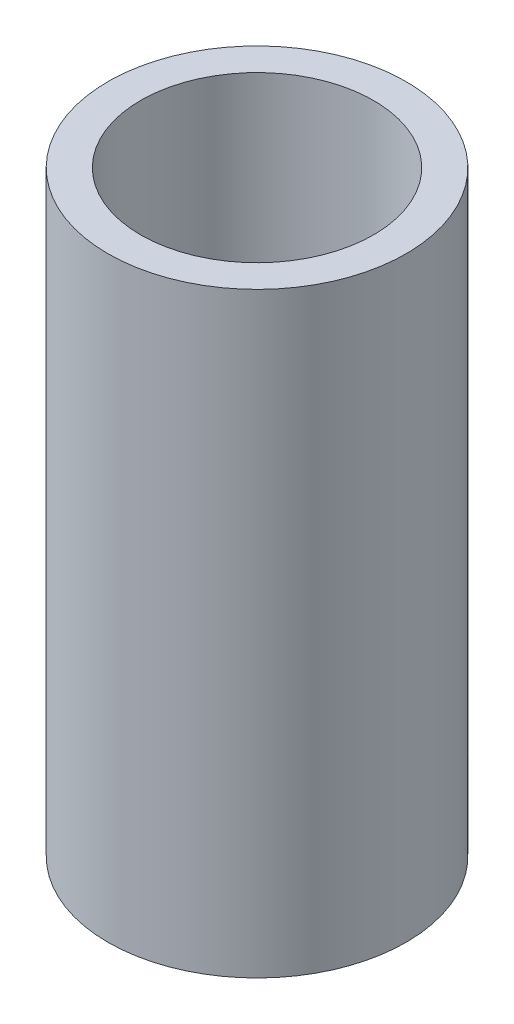
SolidWorks part; units mm, degrees
material "Custom Plastic"
ref_plane "X-Y Datum" through (0, 0, 0) normal (0, 0, 1) x (1, 0, 0)
ref_plane "X-Z Datum" through (0, 0, 0) normal (0, 1, 0) x (1, 0, 0)
ref_plane "Y-Z Datum" through (0, 0, 0) normal (1, 0, 0) x (0, 0, -1)
sketch "Sketch1" plane through (0, 0, 0) normal (0, 1, 0) x (1, 0, 0)
  circle A0 centre (0, 0) radius 3.9688
  circle A1 centre (0, 0) radius 5.08
  dimension "D1" = 7.9375
  dimension "D2" = 10.16
extrude "Boss-Extrude1" add sketch "Sketch1" against normal blind 20.32
